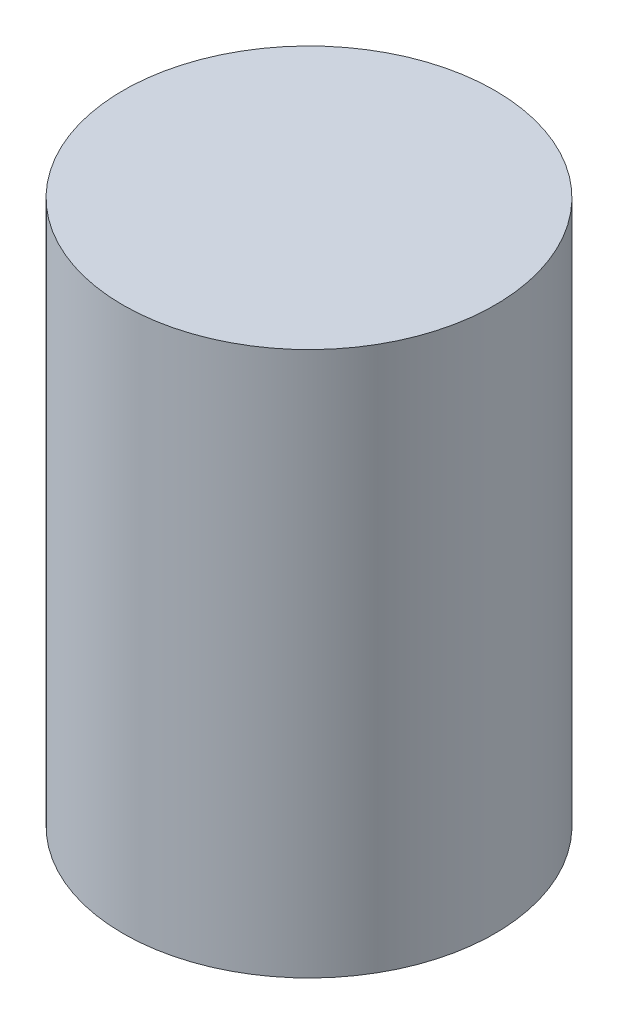
SolidWorks part; units mm, degrees
material "Electronics"
ref_plane "Front Plane" through (0, 0, 0) normal (0, 0, 1) x (1, 0, 0)
ref_plane "Top Plane" through (0, 0, 0) normal (0, 1, 0) x (1, 0, 0)
ref_plane "Right Plane" through (0, 0, 0) normal (1, 0, 0) x (0, 0, -1)
sketch "Sketch1" plane through (0, 0, 0) normal (0, 1, 0) x (1, 0, 0)
  circle A0 centre (0, 0) radius 20.5
  dimension "D1" = 41
extrude "Boss-Extrude1" add sketch "Sketch1" along normal blind 60
